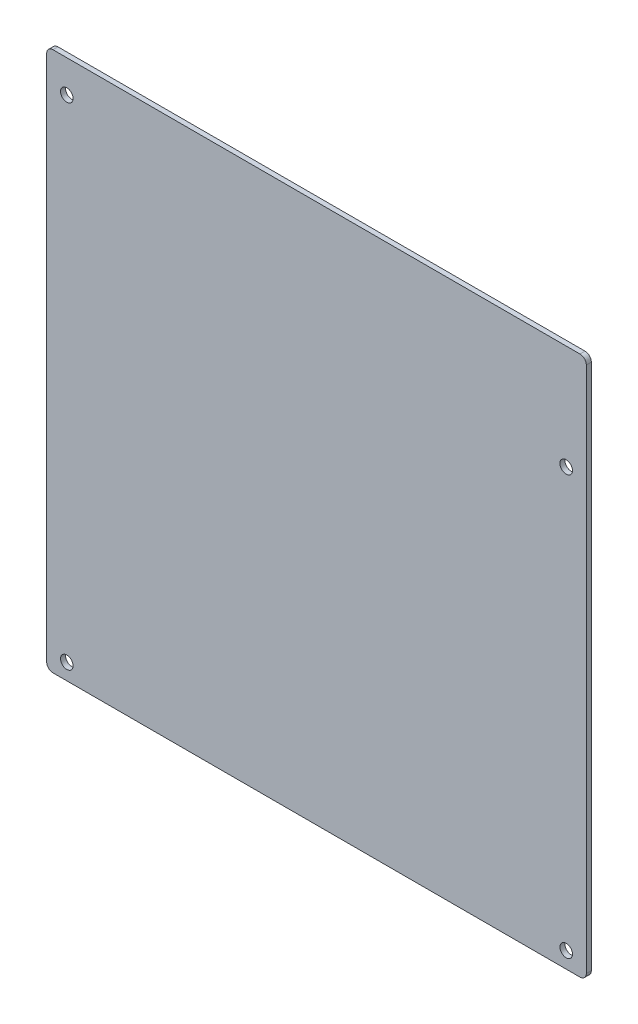
SolidWorks part; units mm, degrees
ref_plane "Alzado" through (0, 0, 0) normal (0, 0, 1) x (1, 0, 0)
ref_plane "Planta" through (0, 0, 0) normal (0, 1, 0) x (1, 0, 0)
ref_plane "Vista lateral" through (0, 0, 0) normal (1, 0, 0) x (0, 0, -1)
sketch "Croquis1" plane through (0, 0, 0) normal (0, 0, 1) x (1, 0, 0)
  line L1 (161.83, 165.1) -> (-4.35, 165.1)
  line L2 (163.83, 163.1) -> (163.83, -3.08)
  line L3 (161.83, -5.08) -> (-4.35, -5.08)
  line L4 (-6.35, 163.1) -> (-6.35, -3.08)
  arc A0 (-4.35, -5.08) -> (-6.35, -3.08) centre (-4.35, -3.08) cw
  arc A1 (163.83, -3.08) -> (161.83, -5.08) centre (161.83, -3.08) cw
  arc A2 (161.83, 165.1) -> (163.83, 163.1) centre (161.83, 163.1) cw
  arc A3 (-4.35, 165.1) -> (-6.35, 163.1) centre (-4.35, 163.1) ccw
  dimension "D1" = 2
extrude "Saliente-Extruir1" add sketch "Croquis1" against normal up to surface (1.575 mm away)
sketch "Croquis2" plane through (0, 0, 0) normal (0, 0, 1) x (1, 0, 0)
  circle A0 centre (0, 0) radius 1.975
  circle A1 centre (157.48, 0) radius 1.975
  circle A2 centre (157.48, 132.08) radius 1.975
  circle A3 centre (0, 154.92) radius 1.975
extrude "Cortar-Extruir1" cut sketch "Croquis2" against normal blind 10
